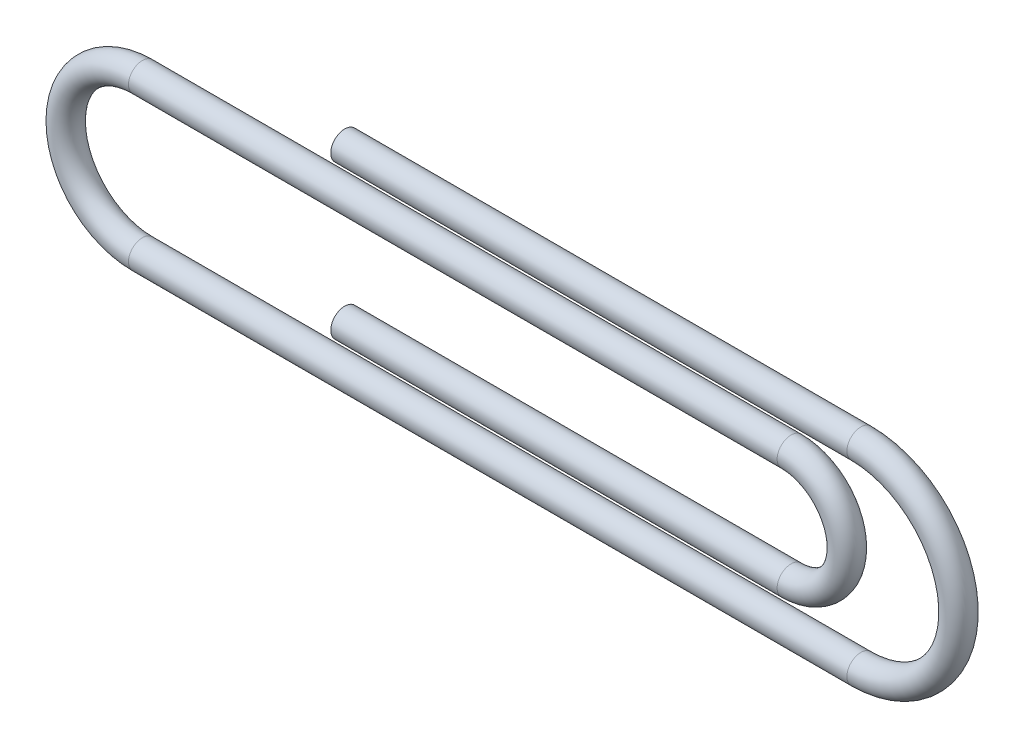
SolidWorks part; units mm, degrees
ref_plane "Front Plane" through (0, 0, 0) normal (0, 0, 1) x (1, 0, 0)
ref_plane "Top Plane" through (0, 0, 0) normal (0, 1, 0) x (1, 0, 0)
ref_plane "Right Plane" through (0, 0, 0) normal (1, 0, 0) x (0, 0, -1)
sketch "Sketch1" plane through (0, 0, 0) normal (0, 0, 1) x (1, 0, 0)
  line L0 (0, 0) -> (18.5, 0)
  line L1 (18.5, -7) -> (-7.25, -7)
  line L2 (-7.25, -1.5) -> (16, -1.5)
  line L3 (16, -5.5) -> (0, -5.5)
  line L4 (0, -5.5) -> (16, -5.5)
  arc A0 (18.5, 0) -> (18.5, -7) centre (18.5, -3.5) cw
  arc A1 (-7.25, -7) -> (-7.25, -1.5) centre (-7.25, -4.25) cw
  arc A2 (16, -1.5) -> (16, -5.5) centre (16, -3.5) cw
  point P11 (-10, -4.25)
  point P13 (22, -3.5)
  point P14 (18, -3.5)
  dimension "D3" = 4
  dimension "D4" = 3.5
  dimension "D5" = 32
  dimension "D1" = 1.5
  dimension "D2" = 1.5
  dimension "D6" = 10
sketch "Sketch2" plane through (0, 0, 0) normal (1, 0, 0) x (0, 0, -1)
  circle A0 centre (0, 0) radius 0.5
  dimension "D1" = 1
sweep "Sweep1" add profiles "Sketch2" path "Sketch1"
